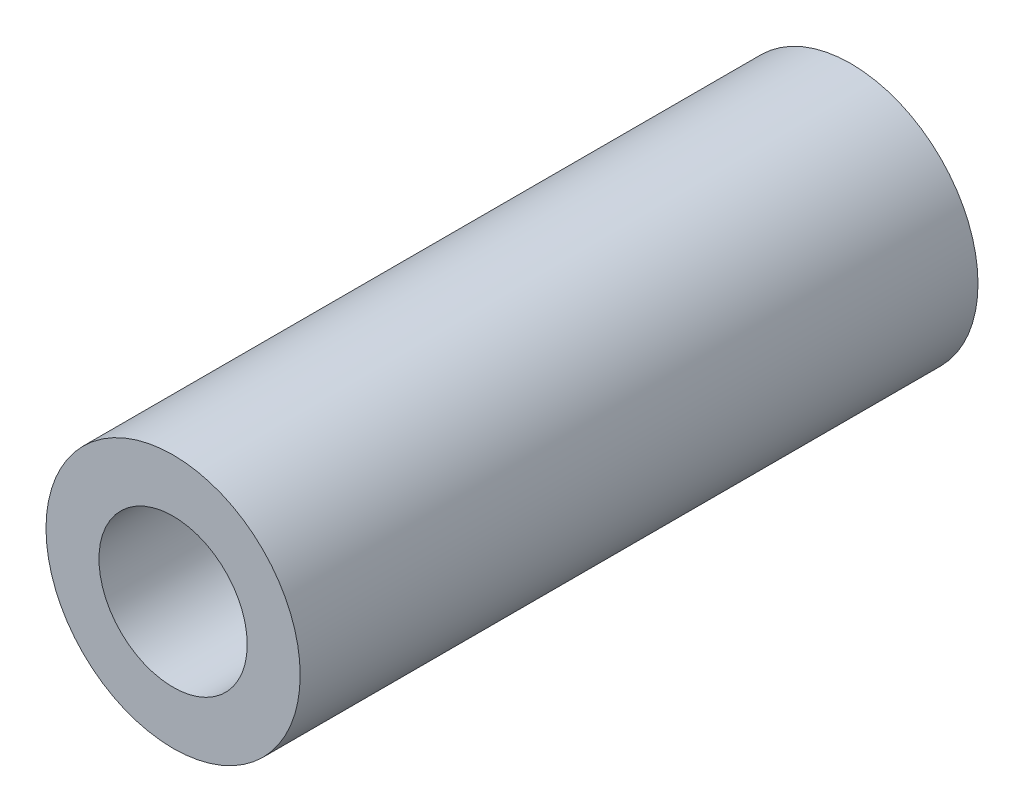
SolidWorks part; units mm, degrees
ref_plane "Plan de face" through (0, 0, 0) normal (0, 0, 1) x (1, 0, 0)
ref_plane "Plan de dessus" through (0, 0, 0) normal (0, 1, 0) x (1, 0, 0)
ref_plane "Plan de droite" through (0, 0, 0) normal (1, 0, 0) x (0, 0, -1)
sketch "Esquisse1" plane through (0, 0, 0) normal (0, 0, 1) x (1, 0, 0)
  circle A0 centre (0, 0) radius 3
  dimension "D1" = 6
extrude "Boss.-Extru.1" add sketch "Esquisse1" along normal blind 16
sketch "Esquisse2" plane through (0, 0, 16) normal (0, 0, 1) x (1, 0, 0)
  circle A0 centre (0, 0) radius 1.75
  dimension "D1" = 3.5
extrude "Enlèv. mat.-Extru.1" cut sketch "Esquisse2" against normal through all
